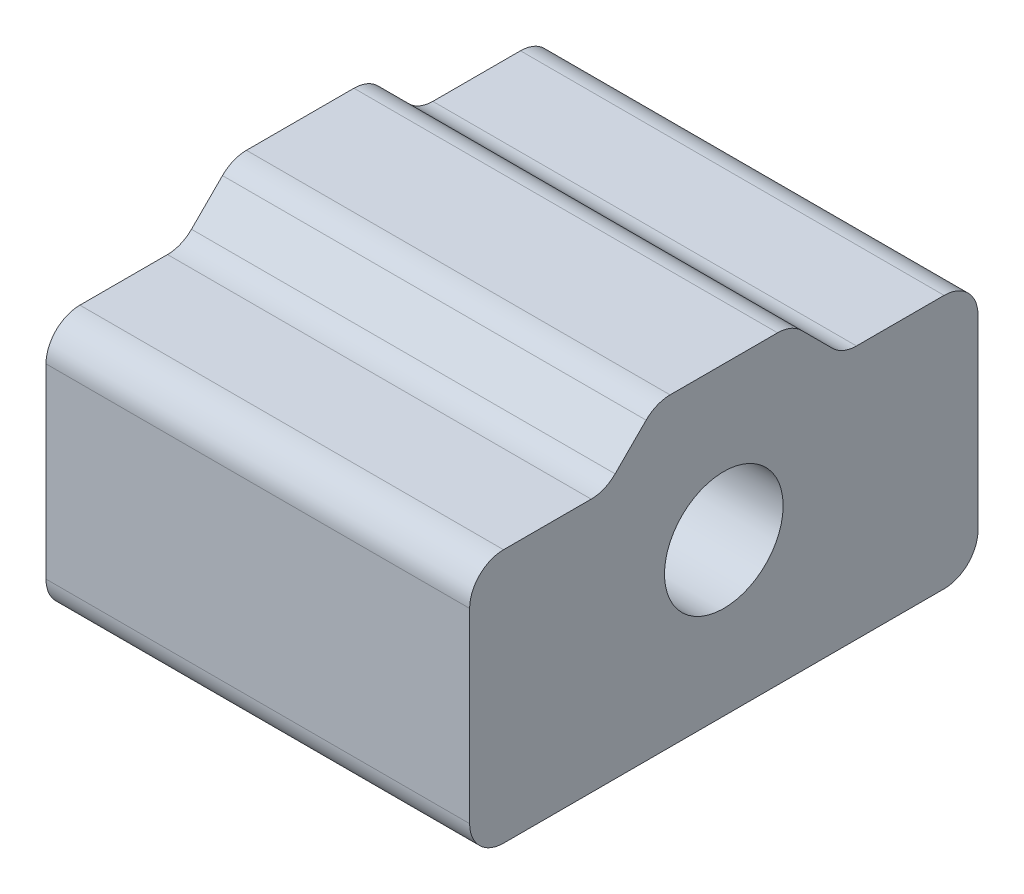
SolidWorks part; units mm, degrees
ref_plane "前视基准面" through (0, 0, 0) normal (0, 0, 1) x (1, 0, 0)
ref_plane "上视基准面" through (0, 0, 0) normal (0, 1, 0) x (1, 0, 0)
ref_plane "右视基准面" through (0, 0, 0) normal (1, 0, 0) x (0, 0, -1)
sketch "草图1" plane through (0, 0, 0) normal (0, 1, 0) x (1, 0, 0)
  line L1 (-31.058, 14.5136) -> (-6.058, 14.5136)
  line L2 (-31.058, 14.5136) -> (-31.058, -15.4864)
  line L3 (-31.058, -15.4864) -> (-6.058, -15.4864)
  line L4 (-6.058, 14.5136) -> (-6.058, -15.4864)
  dimension "D1" = 30
  dimension "D2" = 25
extrude "凸台-拉伸2" add sketch "草图1" along normal blind 18
sketch "草图3" plane through (-6.058, 0, 0) normal (1, 0, 0) x (0, 0, -1)
  line L1 (-15.4864, 15) -> (-7.4864, 15)
  line L2 (-15.4864, 18) -> (-4.4864, 18)
  line L3 (-15.4864, 18) -> (-15.4864, 15)
  line L4 (-15.4864, 15) -> (-7.4864, 15)
  line L6 (-7.4864, 15) -> (-4.4864, 18)
  line L11 (-15.4864, 18) -> (-15.4864, 15)
  line L12 (-7.4864, 15) -> (-4.4864, 18)
  dimension "D1" = 45
  dimension "D2" = 3
  dimension "D3" = 8
extrude "切除-拉伸1" cut sketch "草图3" against normal blind 33
sketch "草图5" plane through (-6.058, 0, 0) normal (1, 0, 0) x (0, 0, -1)
  line L0 (14.5136, 18) -> (14.5136, 15)
  line L1 (14.5136, 18) -> (14.5136, 0) construction
  line L2 (14.5136, 15) -> (6.5136, 15)
  line L6 (14.5136, 18) -> (3.5136, 18)
  line L7 (-4.4864, 18) -> (14.5136, 18) construction
  line L8 (3.5136, 18) -> (6.5136, 15)
  dimension "D1" = 3
  dimension "D2" = 8
  dimension "D3" = 135
extrude "切除-拉伸2" cut sketch "草图5" against normal blind 33
sketch "草图6" plane through (-6.058, 0, 0) normal (1, 0, 0) x (0, 0, -1)
  line L0 (-15.4864, 0) -> (14.5136, 0) construction
  circle A0 centre (-0.4864, 9) radius 3.5
  point P4 (-0.4864, 0)
  point P7 (7.4462, 0)
  point P8 (4.5207, 8.7526)
  dimension "D1" = 0
  dimension "D2" = 9
extrude "切除-拉伸3" cut sketch "草图6" against normal blind 33
sketch "草图8" plane through (0, 0, 0) normal (0, -1, 0) x (1, 0, 0)
  line L0 (-6.058, 15.4864) -> (-6.058, -14.5136) construction
  line L2 (-6.058, -14.5136) -> (-31.058, -14.5136) construction
  line L3 (-31.058, -14.5136) -> (-31.058, 15.4864) construction
  line L4 (-31.058, 15.4864) -> (-6.058, 15.4864) construction
  circle A0 centre (-11.058, 10.4864) radius 2
  circle A1 centre (-11.058, -9.5136) radius 2
  circle A2 centre (-26.058, 10.4864) radius 2
  circle A3 centre (-26.058, -9.5136) radius 2
  point P12 (-5.7891, -18.5136)
  point P17 (0, 0)
  point P19 (-1.058, 9.1695)
  dimension "D1" = 5
  dimension "D2" = 5
  dimension "D3" = 5
  dimension "D4" = 5
  dimension "D5" = 5
  dimension "D6" = 5
  dimension "D7" = 5
  dimension "D8" = 5
extrude "切除-拉伸4" cut sketch "草图8" against normal blind 6
fillet "圆角2" radius 2 8 edges at (-18.558, 18, 4.4864) (-18.558, 15, 7.4864) (-18.558, 15, 15.4864) (-18.558, 0, 15.4864) (-18.558, 0, -14.5136) (-18.558, 15, -14.5136) (-18.558, 15, -6.5136) (-18.558, 18, -3.5136)
